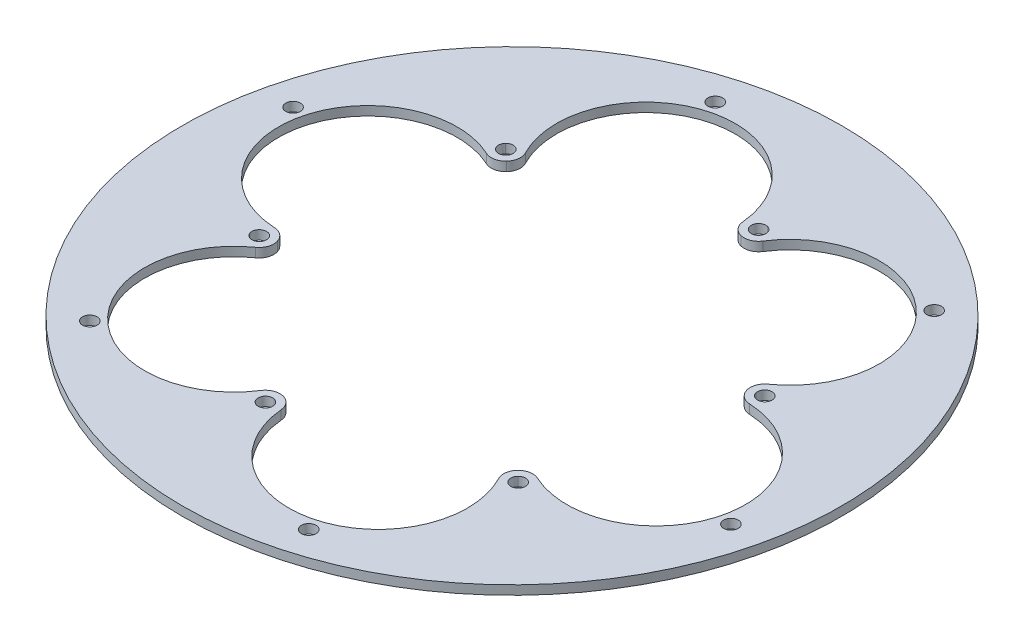
SolidWorks part; units mm, degrees
ref_plane "Front Plane" through (0, 0, 0) normal (0, 0, 1) x (1, 0, 0)
ref_plane "Top Plane" through (0, 0, 0) normal (0, 1, 0) x (1, 0, 0)
ref_plane "Right Plane" through (0, 0, 0) normal (1, 0, 0) x (0, 0, -1)
sketch "Sketch1" plane through (0, 0, 0) normal (0, 1, 0) x (1, 0, 0)
  line L0 (0, 0) -> (-8.9418, 30.7253) construction
  line L1 (-8.9418, 30.7253) -> (-15.0893, 51.849) construction
  line L2 (0, 0) -> (174.3004, 0) construction
  line L3 (0, 0) -> (0, 155.9148) construction
  line L4 (-15.0893, 51.849) -> (-40.4403, 38.7395) construction
  line L5 (-22.9133, 78.7336) -> (-15.0893, 51.849) construction
  line L6 (-40.4403, 38.7395) -> (-13.5514, 46.5647) construction
  line L7 (-13.5514, 46.5647) -> (13.3374, 54.39) construction
  line L8 (-40.4403, 38.7395) -> (-42.1239, 35.111) construction
  line L9 (9.3533, 54.0339) -> (13.3374, 54.39) construction
  line L10 (13.3374, 54.39) -> (16.7051, 52.2317) construction
  line L11 (-15.0893, 51.849) -> (0, 0) construction
  circle A0 centre (0, 0) radius 90.5
  circle A1 centre (0, 0) radius 32 construction
  circle A2 centre (-15.0893, 51.849) radius 22 construction
  circle A3 centre (-40.4403, 38.7395) radius 2
  circle A4 centre (-22.9133, 78.7336) radius 2
  circle A5 centre (13.3374, 54.39) radius 2
  arc A7 (9.3533, 54.0339) -> (-36.8872, 40.5768) centre (-15.0893, 51.849) ccw
  circle A8 centre (-22.9133, 78.7336) radius 6 construction
  arc A9 (-42.1239, 35.111) -> (-36.8872, 40.5768) centre (-40.4403, 38.7395) ccw
  arc A10 (9.3533, 54.0339) -> (16.7051, 52.2317) centre (13.3374, 54.39) ccw
  arc A11 (-36.5137, 39.8822) -> (-16.6032, 27.3557) centre (-15.0893, 51.849) ccw construction
  arc A12 (-36.8872, 40.5768) -> (-36.5137, 39.8822) centre (-15.0893, 51.849) ccw construction
  circle A13 centre (-15.0893, 51.849) radius 24.54 construction
  arc A14 (-16.6032, 27.3557) -> (-8.232, 28.2865) centre (-15.0893, 51.849) ccw construction
  arc A15 (-8.232, 28.2865) -> (-0.6687, 31.993) centre (-15.0893, 51.849) ccw construction
  arc A16 (-0.6687, 31.993) -> (0, 32.4963) centre (-15.0893, 51.849) ccw construction
  arc A17 (0, 32.4963) -> (9.4109, 53.2473) centre (-15.0893, 51.849) ccw construction
  arc A18 (9.4109, 53.2473) -> (9.3533, 54.0339) centre (-15.0893, 51.849) ccw construction
  arc A19 (9.3451, 54.0359) -> (16.6969, 52.2337) centre (13.3292, 54.392) ccw
  arc A20 (16.7051, 52.2317) -> (9.3533, 54.0339) centre (13.3374, 54.39) ccw construction
  circle A21 centre (13.3374, 54.39) radius 4 construction
  arc A22 (-36.8872, 40.5768) -> (-42.1239, 35.111) centre (-40.4403, 38.7395) ccw construction
  circle A23 centre (-40.4403, 38.7395) radius 4 construction
  arc A24 (51.4713, 18.9168) -> (16.6969, 52.2337) centre (37.3579, 38.9922) ccw
  arc A25 (51.4713, 18.9168) -> (53.5865, 11.6488) centre (53.7718, 15.6445) ccw
  arc A26 (51.469, 18.9248) -> (53.5842, 11.6569) centre (53.7695, 15.6526) ccw
  arc A27 (42.1181, -35.1171) -> (53.5842, 11.6569) centre (52.4471, -12.8568) ccw
  arc A28 (42.1181, -35.1171) -> (36.8814, -40.5829) centre (40.4345, -38.7455) ccw
  arc A29 (42.1239, -35.111) -> (36.8872, -40.5768) centre (40.4403, -38.7395) ccw
  arc A30 (-9.3533, -54.0339) -> (36.8872, -40.5768) centre (15.0893, -51.849) ccw
  arc A31 (-9.3533, -54.0339) -> (-16.7051, -52.2317) centre (-13.3374, -54.39) ccw
  arc A32 (-9.3451, -54.0359) -> (-16.6969, -52.2337) centre (-13.3292, -54.392) ccw
  arc A33 (-51.4713, -18.9168) -> (-16.6969, -52.2337) centre (-37.3579, -38.9922) ccw
  arc A34 (-51.4713, -18.9168) -> (-53.5865, -11.6488) centre (-53.7718, -15.6445) ccw
  arc A35 (-51.469, -18.9248) -> (-53.5842, -11.6569) centre (-53.7695, -15.6526) ccw
  arc A36 (-42.1181, 35.1171) -> (-53.5842, -11.6569) centre (-52.4471, 12.8568) ccw
  arc A37 (-42.1181, 35.1171) -> (-36.8814, 40.5829) centre (-40.4345, 38.7455) ccw
  circle A38 centre (13.3292, 54.392) radius 2
  circle A39 centre (53.7718, 15.6445) radius 2
  circle A40 centre (56.7286, 59.2103) radius 2
  circle A41 centre (53.7695, 15.6526) radius 2
  circle A42 centre (40.4345, -38.7455) radius 2
  circle A43 centre (79.642, -19.5233) radius 2
  circle A44 centre (40.4403, -38.7395) radius 2
  circle A45 centre (-13.3374, -54.39) radius 2
  circle A46 centre (22.9133, -78.7336) radius 2
  circle A47 centre (-13.3292, -54.392) radius 2
  circle A48 centre (-53.7718, -15.6445) radius 2
  circle A49 centre (-56.7286, -59.2103) radius 2
  circle A50 centre (-53.7695, -15.6526) radius 2
  circle A51 centre (-40.4345, 38.7455) radius 2
  circle A52 centre (-79.642, 19.5233) radius 2
  point P20 (9.223, 55.7573)
  point P24 (-41.6806, 32.3951)
  point P34 (0.9433, 56.2528)
  point P78 (0, 0)
  dimension "D1" = 181
  dimension "D2" = 64
  dimension "D3" = 44
  dimension "D5" = 4
  dimension "D7" = 12
  dimension "D6" = 28.54
  dimension "D8" = 78.882
  dimension "D9" = 142.236
  dimension "D10" = 142.236
  dimension "D4" = 2.54
  dimension "D11" = 6
extrude "Boss-Extrude1" add sketch "Sketch1" along normal blind 2.5 contours A0 A5 A4 A3 A36 A37 A9 A7 A10 A19 A24 A25 A26 A27 A28 A29 A30 A31 A32 A33 A34 A35
